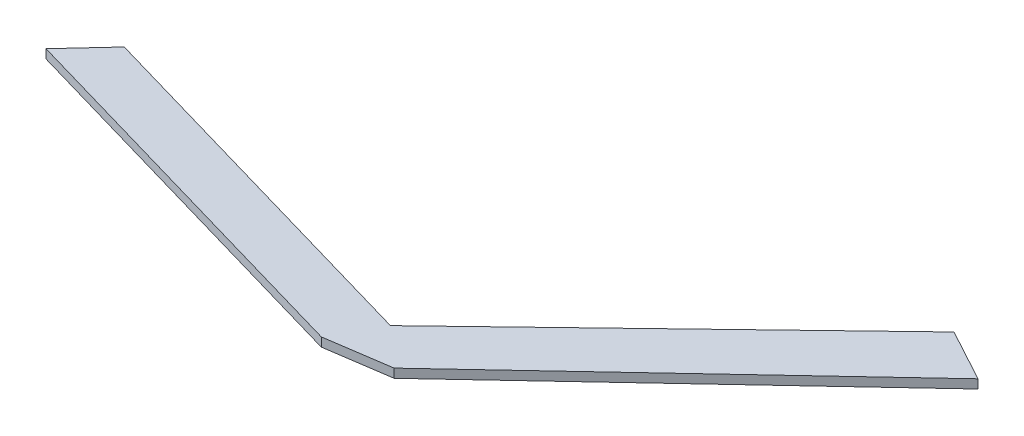
SolidWorks part; units mm, degrees
ref_plane "Front Plane" through (0, 0, 0) normal (0, 0, 1) x (1, 0, 0)
ref_plane "Top Plane" through (0, 0, 0) normal (0, 1, 0) x (1, 0, 0)
ref_plane "Right Plane" through (0, 0, 0) normal (1, 0, 0) x (0, 0, -1)
sketch "Sketch1" plane through (0, 0, 0) normal (0, 1, 0) x (1, 0, 0)
  line L0 (0, 0) -> (-42.2696, 12.2179)
  line L1 (-42.2696, 12.2179) -> (-46.5175, 7.6334)
  line L2 (-46.5175, 7.6334) -> (-2.8069, -5.001)
  line L3 (-2.8069, -5.001) -> (4.3649, -3.9392)
  line L4 (4.3649, -3.9392) -> (38.3682, 27.969)
  line L5 (38.3682, 27.969) -> (32.4367, 31.1907)
  line L6 (32.4367, 31.1907) -> (0, 0)
  point P5 (10.3726, 23.5065)
  point P9 (28.1023, 5.0676)
  point P10 (2.9261, -2.2016)
  point P11 (45.3002, 10.6524)
  point P12 (-4.0771, 0)
  point P13 (2.1931, -5.2151)
  point P14 (43.1697, 12.7033)
  point P15 (47.1117, 7.9227)
  point P16 (1.468, -5.6917)
  point P17 (-5.1002, -2.6224)
  point P18 (-5.1002, -2.6224)
  point P19 (-5.1002, -2.6224)
  point P20 (4.3649, -3.9392)
  dimension "D1" = 120
  dimension "D2" = 7.25
  dimension "D3" = 45
  dimension "D4" = 44
  dimension "D5" = 6.25
  dimension "D6" = 6.75
  dimension "D7" = 46.63
  dimension "D8" = 45.5
extrude "Boss-Extrude1" add sketch "Sketch1" along normal blind 1
